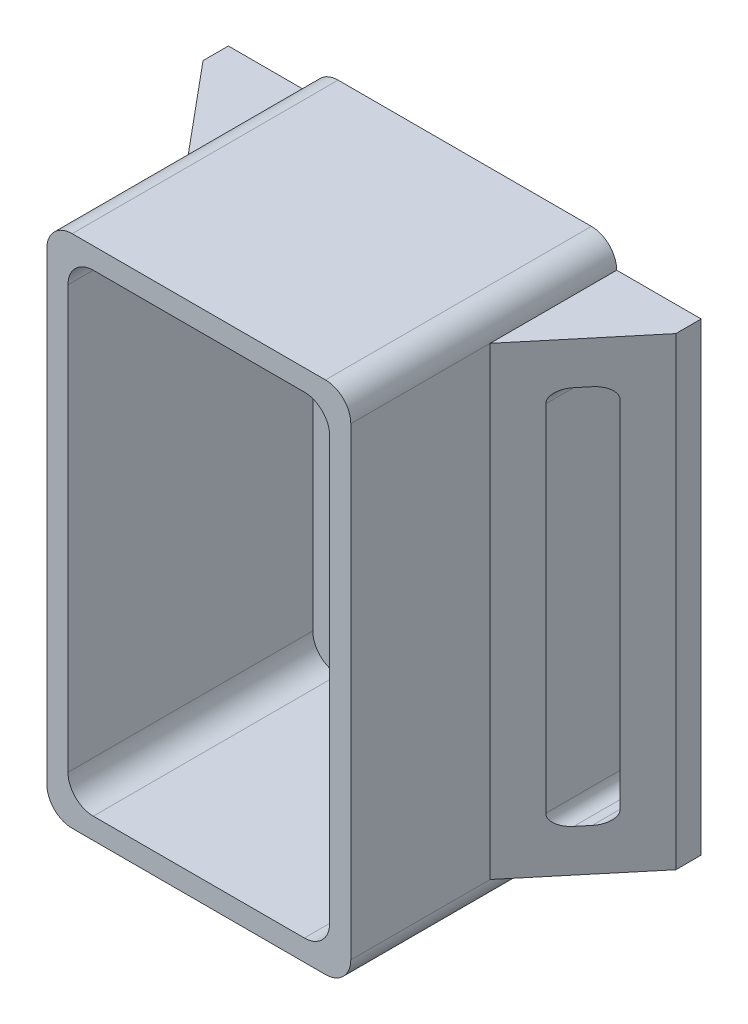
SolidWorks part; units mm, degrees
ref_plane "Front Plane" through (0, 0, 0) normal (0, 0, 1) x (1, 0, 0)
ref_plane "Top Plane" through (0, 0, 0) normal (0, 1, 0) x (1, 0, 0)
ref_plane "Right Plane" through (0, 0, 0) normal (1, 0, 0) x (0, 0, -1)
sketch "Sketch1" plane through (0, 0, 0) normal (0, 0, 1) x (1, 0, 0)
  line L0 (0.0095, 35.9354) -> (0.0095, -20.0646) construction
  line L1 (-12.4905, 35.9354) -> (12.5095, 35.9354)
  line L2 (-15.4905, 32.9354) -> (-15.4905, -17.0646)
  line L3 (-12.4905, -20.0646) -> (12.5095, -20.0646)
  line L4 (15.5095, 32.9354) -> (15.5095, -17.0646)
  line L5 (-14.9905, 38.4354) -> (15.0095, 38.4354)
  line L6 (-17.9905, 35.4354) -> (-17.9905, -19.5646)
  line L7 (-14.9905, -22.5646) -> (15.0095, -22.5646)
  line L8 (18.0095, 35.4354) -> (18.0095, -19.5646)
  line L9 (-17.9905, 38.4354) -> (18.0095, -22.5646) construction
  line L10 (-17.9905, -22.5646) -> (18.0095, 38.4354) construction
  line L11 (15.5095, 7.9354) -> (-15.4905, 7.9354) construction
  arc A0 (-12.4905, 35.9354) -> (-15.4905, 32.9354) centre (-12.4905, 32.9354) ccw
  arc A1 (-15.4905, -17.0646) -> (-12.4905, -20.0646) centre (-12.4905, -17.0646) ccw
  arc A2 (12.5095, -20.0646) -> (15.5095, -17.0646) centre (12.5095, -17.0646) ccw
  arc A3 (12.5095, 35.9354) -> (15.5095, 32.9354) centre (12.5095, 32.9354) cw
  arc A4 (-17.9905, -19.5646) -> (-14.9905, -22.5646) centre (-14.9905, -19.5646) ccw
  arc A5 (15.0095, -22.5646) -> (18.0095, -19.5646) centre (15.0095, -19.5646) ccw
  arc A6 (15.0095, 38.4354) -> (18.0095, 35.4354) centre (15.0095, 35.4354) cw
  arc A7 (-14.9905, 38.4354) -> (-17.9905, 35.4354) centre (-14.9905, 35.4354) ccw
  point P6 (-15.4905, 35.9354)
  point P11 (15.5095, -20.0646)
  point P14 (15.5095, 35.9354)
  point P15 (0.0095, 7.9354)
  dimension "D3" = 3
  dimension "D6" = 3
  dimension "D1" = 31
  dimension "D2" = 56
  dimension "D4" = 36
  dimension "D5" = 61
extrude "Shell" add sketch "Sketch1" along normal blind 29
sketch "Sketch3" plane through (0, 0, 0) normal (0, 0, -1) x (-1, 0, 0)
  line L1 (-15.0095, 38.4354) -> (14.9905, 38.4354)
  line L2 (-18.0095, 35.4354) -> (-18.0095, -19.5646)
  line L3 (-15.0095, -22.5646) -> (14.9905, -22.5646)
  line L4 (17.9905, 35.4354) -> (17.9905, -19.5646)
  line L7 (17.9905, 35.4354) -> (17.9905, -19.5646) construction
  arc A0 (-18.0095, -19.5646) -> (-15.0095, -22.5646) centre (-15.0095, -19.5646) ccw
  arc A1 (14.9905, -22.5646) -> (17.9905, -19.5646) centre (14.9905, -19.5646) ccw
  arc A2 (14.9905, 38.4354) -> (17.9905, 35.4354) centre (14.9905, 35.4354) cw
  arc A3 (-15.0095, 38.4354) -> (-18.0095, 35.4354) centre (-15.0095, 35.4354) ccw
  arc A4 (14.9905, -22.5646) -> (17.9905, -19.5646) centre (14.9905, -19.5646) ccw construction
  dimension "D1" = 3
  dimension "D2" = 36
extrude "Bottom cover" add sketch "Sketch3" along normal blind 2.5
sketch "Sketch4" plane through (0, 0, -2.5) normal (0, 0, -1) x (-1, 0, 0)
  line L0 (-0.0095, 38.4354) -> (-0.0095, -22.5646) construction
  line L1 (14.9905, 38.4354) -> (-15.0095, 38.4354) construction
  line L2 (-15.0095, -22.5646) -> (14.9905, -22.5646) construction
  line L3 (17.9905, 7.9354) -> (-18.0095, 7.9354) construction
  line L4 (17.9905, -19.5646) -> (17.9905, 35.4354) construction
  line L5 (-18.0095, 35.4354) -> (-18.0095, -19.5646) construction
sketch3d "3DSketch1"
  line L0 (18.0095, 35.4354, -2.5) -> (28.0095, 35.4354, -2.5)
  line L1 (28.0095, 35.4354, -2.5) -> (28.0095, 35.4354, 0.5)
  line L5 (28.0095, 35.4354, 0.5) -> (18.0095, 35.4354, 12.5)
  line L7 (-17.9905, 35.4354, -2.5) -> (-27.9905, 35.4354, -2.5)
  line L8 (18.0095, 35.4354, 12.5) -> (18.0095, 35.4354, -2.5)
  line L9 (-27.9905, 35.4354, -2.5) -> (-27.9905, 35.4354, 0.5)
  line L14 (-27.9905, 35.4354, 0.5) -> (-17.9905, 35.4354, 12.5)
  line L15 (-17.9905, 35.4354, 29) -> (-17.9905, 35.4354, -2.5) construction
  line L16 (-17.9905, 35.4354, 12.5) -> (-17.9905, 35.4354, -2.5)
  point P11 (18.0102, 35.4354, -2.4976)
  point P12 (18.0095, 35.4354, -2.5)
  dimension "D1" = 3
  dimension "D2" = 10
  dimension "D3" = 15
  dimension "D4" = 3
  dimension "D6" = 15
  dimension "D5" = 3
extrude "Boss-Extrude4" add sketch "3DSketch1" along direction (0, -1, 0) on the side against the normal blind 55
sketch "Sketch9" plane through (0, 0, -2.5) normal (0, 0, -1) x (-1, 0, 0)
  line L0 (-18.0095, 35.4354) -> (-18.0095, -19.5646) construction
  line L1 (-21.0095, 7.9354) -> (-21.0095, 30.4354) construction
  line L2 (-21.0095, 7.9354) -> (-21.0095, -14.5646) construction
  line L3 (-21.0095, -14.5646) -> (-25.0095, -14.5646) construction
  line L5 (-23.5095, -14.5646) -> (-22.5095, -14.5646)
  line L6 (-25.0095, -13.0646) -> (-25.0095, 28.9354)
  line L7 (-23.5095, 30.4354) -> (-22.5095, 30.4354)
  line L8 (-21.0095, -13.0646) -> (-21.0095, 28.9354)
  line L12 (17.9905, 7.9354) -> (20.9905, 7.9354) construction
  line L13 (20.9905, 30.4354) -> (24.9905, 30.4354) construction
  line L14 (24.9905, 30.4354) -> (24.9905, -14.5646) construction
  line L15 (-18.0095, -19.5646) -> (17.9905, -19.5646) construction
  line L16 (22.4905, 30.4354) -> (23.4905, 30.4354)
  line L17 (20.9905, 28.9354) -> (20.9905, -13.0646)
  line L18 (22.4905, -14.5646) -> (23.4905, -14.5646)
  line L19 (24.9905, 28.9354) -> (24.9905, -13.0646)
  line L20 (17.9905, -19.5646) -> (17.9905, 35.4354) construction
  line L21 (17.9905, 35.4354) -> (-18.0095, 35.4354) construction
  line L22 (-18.0095, 7.9354) -> (-21.0095, 7.9354) construction
  line L23 (-18.0095, -19.5646) -> (-28.0095, -19.5646) construction
  arc A0 (24.9905, -13.0646) -> (23.4905, -14.5646) centre (23.4905, -13.0646) cw
  arc A1 (20.9905, -13.0646) -> (22.4905, -14.5646) centre (22.4905, -13.0646) ccw
  arc A2 (23.4905, 30.4354) -> (24.9905, 28.9354) centre (23.4905, 28.9354) cw
  arc A3 (22.4905, 30.4354) -> (20.9905, 28.9354) centre (22.4905, 28.9354) ccw
  arc A4 (-25.0095, -13.0646) -> (-23.5095, -14.5646) centre (-23.5095, -13.0646) ccw
  arc A5 (-22.5095, -14.5646) -> (-21.0095, -13.0646) centre (-22.5095, -13.0646) ccw
  arc A6 (-25.0095, 28.9354) -> (-23.5095, 30.4354) centre (-23.5095, 28.9354) cw
  arc A7 (-21.0095, 28.9354) -> (-22.5095, 30.4354) centre (-22.5095, 28.9354) ccw
  dimension "D2" = 1.5
  dimension "D1" = 4
  dimension "D3" = 4
  dimension "D4" = 3
  dimension "D5" = 42
  dimension "D6" = 42
  dimension "D7" = 5
extrude "Cut-Extrude1" cut sketch "Sketch9" against normal blind 64
